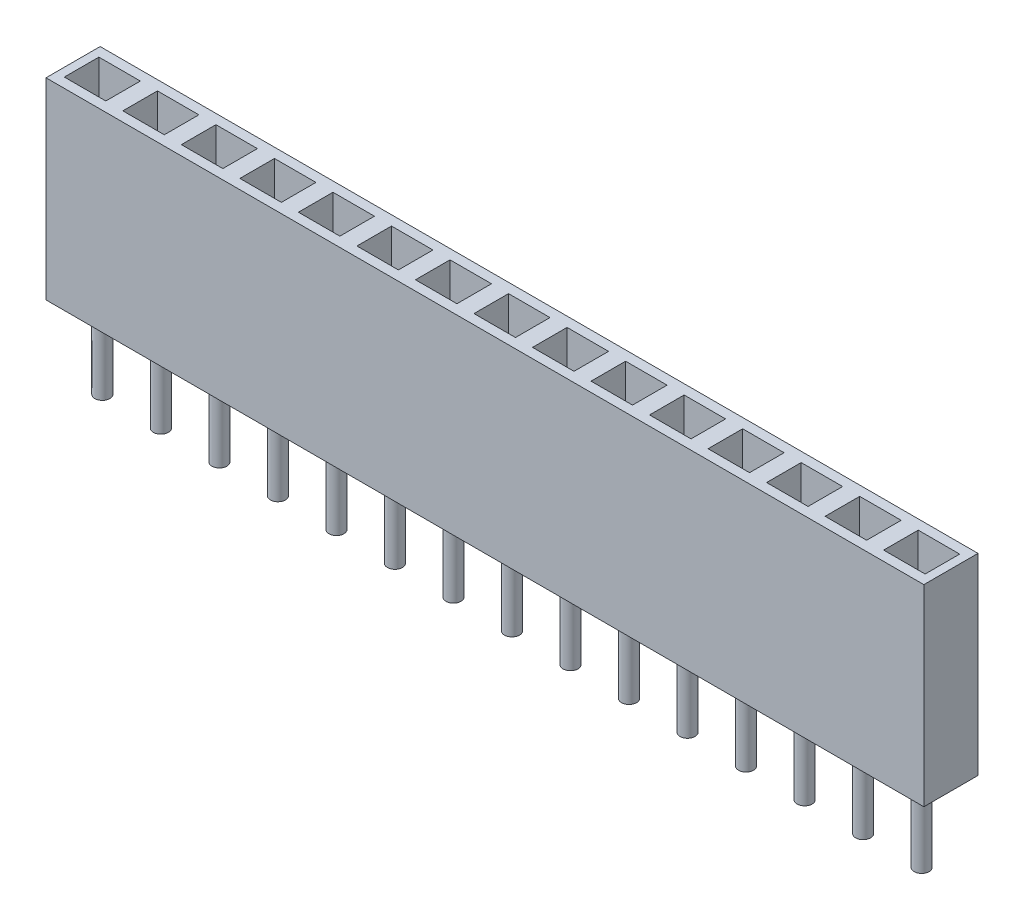
SolidWorks part; units mm, degrees
ref_plane "Plan de face" through (0, 0, 0) normal (0, 0, 1) x (1, 0, 0)
ref_plane "Plan de dessus" through (0, 0, 0) normal (0, 1, 0) x (1, 0, 0)
ref_plane "Plan de droite" through (0, 0, 0) normal (1, 0, 0) x (0, 0, -1)
sketch "Esquisse1" plane through (0, 0, 0) normal (0, 1, 0) x (1, 0, 0)
  line L1 (0, 0) -> (2.54, 0)
  line L2 (0, 0) -> (0, 2.35)
  line L3 (0, 2.35) -> (2.54, 2.35)
  line L4 (2.54, 0) -> (2.54, 2.35)
  dimension "D1" = 2.35
  dimension "D2" = 2.54
extrude "Boss.-Extru.1" add sketch "Esquisse1" along normal blind 8.35
sketch "Esquisse3" plane through (0, 8.35, 0) normal (0, 1, 0) x (1, 0, 0)
  line L0 (0, 1.175) -> (2.54, 1.175) construction
  line L1 (0, 2.35) -> (0, 0) construction
  line L2 (2.54, 0) -> (2.54, 2.35) construction
  line L3 (1.27, 2.35) -> (1.27, 0) construction
  line L6 (2.54, 2.35) -> (0, 2.35) construction
  line L7 (0, 0) -> (2.54, 0) construction
  line L9 (0.37, 1.925) -> (2.17, 1.925)
  line L10 (0.37, 1.925) -> (0.37, 0.425)
  line L11 (0.37, 0.425) -> (2.17, 0.425)
  line L12 (2.17, 1.925) -> (2.17, 0.425)
  point P16 (1.27, 1.925)
  point P17 (2.17, 1.175)
  dimension "D1" = 1.8
  dimension "D2" = 1.5
extrude "Enlèv. mat.-Extru.1" cut sketch "Esquisse3" against normal blind 5.5
sketch "Esquisse2" plane through (0, 0, 0) normal (0, -1, 0) x (1, 0, 0)
  line L0 (1.27, 0) -> (1.27, -2.35) construction
  line L1 (0, 0) -> (2.54, 0) construction
  line L2 (2.54, -2.35) -> (0, -2.35) construction
  circle A0 centre (1.27, -1.175) radius 0.325
  dimension "D1" = 0.65
extrude "Boss.-Extru.2" add sketch "Esquisse2" along normal blind 3.5
sketch "Esquisse4" plane through (0, 2.85, 0) normal (0, 1, 0) x (1, 0, 0)
  line L0 (1.27, 1.925) -> (1.27, 0.425) construction
  line L1 (2.17, 1.925) -> (0.37, 1.925) construction
  line L2 (0.37, 0.425) -> (2.17, 0.425) construction
  circle A0 centre (1.27, 1.175) radius 0.325
  dimension "D1" = 0.65
extrude "Enlèv. mat.-Extru.3" cut sketch "Esquisse4" against normal blind 2
pattern_linear "Répétition linéaire1" count 15 spacing 2.54 along (1, 0, 0) of "Boss.-Extru.1", "Enlèv. mat.-Extru.1", "Boss.-Extru.2", "Enlèv. mat.-Extru.3"
